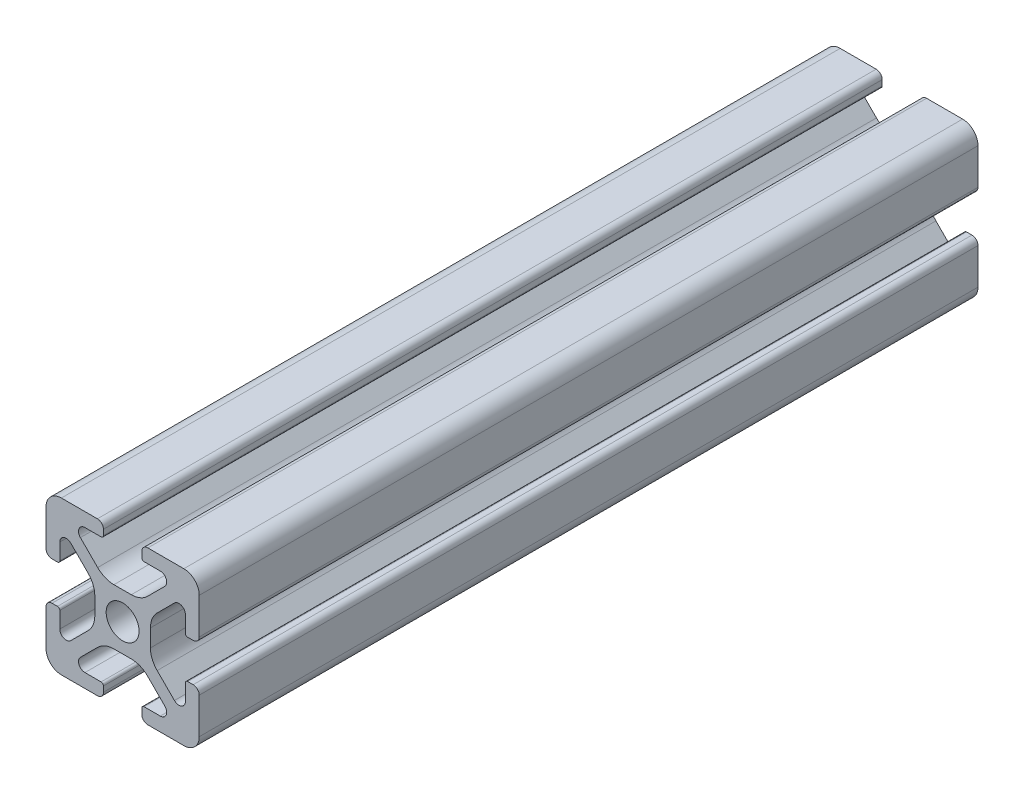
SolidWorks part; units mm, degrees
material "1060 Alloy"
ref_plane "Front Plane" through (0, 0, 0) normal (0, 0, 1) x (1, 0, 0)
ref_plane "Top Plane" through (0, 0, 0) normal (0, 1, 0) x (1, 0, 0)
ref_plane "Right Plane" through (0, 0, 0) normal (1, 0, 0) x (0, 0, -1)
sketch "Sketch1" plane through (0, 0, 0) normal (0, 0, 1) x (1, 0, 0)
  line L2 (-9.9949, 7.9883) -> (-9.9949, 3.2893)
  line L3 (-7.9883, 9.9949) -> (-3.2893, 9.9949)
  line L4 (-2.5019, 9.2075) -> (-2.5019, 8.4963)
  line L5 (-2.8067, 8.1915) -> (-4.9149, 8.1915)
  line L6 (-5.5076, 6.7606) -> (-3.2528, 4.5058)
  line L7 (-6.7606, 5.5076) -> (-4.5058, 3.2528)
  line L8 (-8.1915, 4.9149) -> (-8.1915, 2.8067)
  line L9 (-8.4963, 2.5019) -> (-9.2075, 2.5019)
  line L11 (-1.1334, 3.6279) -> (1.1334, 3.6279)
  line L12 (-3.6279, 1.1334) -> (-3.6279, -1.1334)
  line L13 (8.4963, 2.5019) -> (9.2075, 2.5019)
  line L14 (8.1915, 4.9149) -> (8.1915, 2.8067)
  line L15 (9.9949, 7.9883) -> (9.9949, 3.2893)
  line L16 (7.9883, 9.9949) -> (3.2893, 9.9949)
  line L17 (2.5019, 9.2075) -> (2.5019, 8.4963)
  line L18 (2.8067, 8.1915) -> (4.9149, 8.1915)
  line L19 (3.6279, 1.1334) -> (3.6279, -1.1334)
  line L20 (5.5076, 6.7606) -> (3.2528, 4.5058)
  line L21 (6.7606, 5.5076) -> (4.5058, 3.2528)
  line L22 (-8.4963, -2.5019) -> (-9.2075, -2.5019)
  line L23 (-8.1915, -4.9149) -> (-8.1915, -2.8067)
  line L24 (-6.7606, -5.5076) -> (-4.5058, -3.2528)
  line L25 (-5.5076, -6.7606) -> (-3.2528, -4.5058)
  line L26 (-2.8067, -8.1915) -> (-4.9149, -8.1915)
  line L27 (-2.5019, -9.2075) -> (-2.5019, -8.4963)
  line L28 (-7.9883, -9.9949) -> (-3.2893, -9.9949)
  line L29 (-9.9949, -7.9883) -> (-9.9949, -3.2893)
  line L30 (9.9949, -7.9883) -> (9.9949, -3.2893)
  line L31 (7.9883, -9.9949) -> (3.2893, -9.9949)
  line L32 (2.5019, -9.2075) -> (2.5019, -8.4963)
  line L33 (2.8067, -8.1915) -> (4.9149, -8.1915)
  line L34 (5.5076, -6.7606) -> (3.2528, -4.5058)
  line L35 (6.7606, -5.5076) -> (4.5058, -3.2528)
  line L36 (8.1915, -4.9149) -> (8.1915, -2.8067)
  line L37 (8.4963, -2.5019) -> (9.2075, -2.5019)
  line L38 (-1.1334, -3.6279) -> (1.1334, -3.6279)
  circle A0 centre (0, 0) radius 2.1463
  arc A1 (-9.9949, 7.9883) -> (-7.9883, 9.9949) centre (-7.9883, 7.9883) cw
  arc A2 (-6.7606, 5.5076) -> (-8.1915, 4.9149) centre (-7.3533, 4.9149) ccw
  arc A3 (-4.9149, 8.1915) -> (-5.5076, 6.7606) centre (-4.9149, 7.3533) ccw
  arc A4 (-3.2893, 9.9949) -> (-2.5019, 9.2075) centre (-3.2893, 9.2075) cw
  arc A5 (-9.9949, 3.2893) -> (-9.2075, 2.5019) centre (-9.2075, 3.2893) ccw
  arc A6 (-8.1915, 2.8067) -> (-8.4963, 2.5019) centre (-8.4963, 2.8067) cw
  arc A7 (-2.5019, 8.4963) -> (-2.8067, 8.1915) centre (-2.8067, 8.4963) cw
  arc A8 (-1.1334, 3.6279) -> (-3.2528, 4.5058) centre (-1.1334, 6.6251) cw
  arc A9 (-3.6279, 1.1334) -> (-4.5058, 3.2528) centre (-6.6251, 1.1334) ccw
  arc A10 (8.1915, 2.8067) -> (8.4963, 2.5019) centre (8.4963, 2.8067) ccw
  arc A11 (9.9949, 3.2893) -> (9.2075, 2.5019) centre (9.2075, 3.2893) cw
  arc A12 (9.9949, 7.9883) -> (7.9883, 9.9949) centre (7.9883, 7.9883) ccw
  arc A13 (3.2893, 9.9949) -> (2.5019, 9.2075) centre (3.2893, 9.2075) ccw
  arc A14 (2.5019, 8.4963) -> (2.8067, 8.1915) centre (2.8067, 8.4963) ccw
  arc A15 (1.1334, 3.6279) -> (3.2528, 4.5058) centre (1.1334, 6.6251) ccw
  arc A16 (3.6279, 1.1334) -> (4.5058, 3.2528) centre (6.6251, 1.1334) cw
  arc A17 (6.7606, 5.5076) -> (8.1915, 4.9149) centre (7.3533, 4.9149) cw
  arc A18 (4.9149, 8.1915) -> (5.5076, 6.7606) centre (4.9149, 7.3533) cw
  arc A19 (-3.6279, -1.1334) -> (-4.5058, -3.2528) centre (-6.6251, -1.1334) cw
  arc A20 (-1.1334, -3.6279) -> (-3.2528, -4.5058) centre (-1.1334, -6.6251) ccw
  arc A21 (-2.5019, -8.4963) -> (-2.8067, -8.1915) centre (-2.8067, -8.4963) ccw
  arc A22 (-8.1915, -2.8067) -> (-8.4963, -2.5019) centre (-8.4963, -2.8067) ccw
  arc A23 (-9.9949, -3.2893) -> (-9.2075, -2.5019) centre (-9.2075, -3.2893) cw
  arc A24 (-3.2893, -9.9949) -> (-2.5019, -9.2075) centre (-3.2893, -9.2075) ccw
  arc A25 (-4.9149, -8.1915) -> (-5.5076, -6.7606) centre (-4.9149, -7.3533) cw
  arc A26 (-6.7606, -5.5076) -> (-8.1915, -4.9149) centre (-7.3533, -4.9149) cw
  arc A27 (-9.9949, -7.9883) -> (-7.9883, -9.9949) centre (-7.9883, -7.9883) ccw
  arc A28 (9.9949, -7.9883) -> (7.9883, -9.9949) centre (7.9883, -7.9883) cw
  arc A29 (6.7606, -5.5076) -> (8.1915, -4.9149) centre (7.3533, -4.9149) ccw
  arc A30 (4.9149, -8.1915) -> (5.5076, -6.7606) centre (4.9149, -7.3533) ccw
  arc A31 (3.2893, -9.9949) -> (2.5019, -9.2075) centre (3.2893, -9.2075) cw
  arc A32 (9.9949, -3.2893) -> (9.2075, -2.5019) centre (9.2075, -3.2893) ccw
  arc A33 (8.1915, -2.8067) -> (8.4963, -2.5019) centre (8.4963, -2.8067) cw
  arc A34 (2.5019, -8.4963) -> (2.8067, -8.1915) centre (2.8067, -8.4963) cw
  arc A35 (1.1334, -3.6279) -> (3.2528, -4.5058) centre (1.1334, -6.6251) cw
  arc A36 (3.6279, -1.1334) -> (4.5058, -3.2528) centre (6.6251, -1.1334) ccw
extrude "Boss-Extrude1" add sketch "Sketch1" along normal mid plane 101.6
